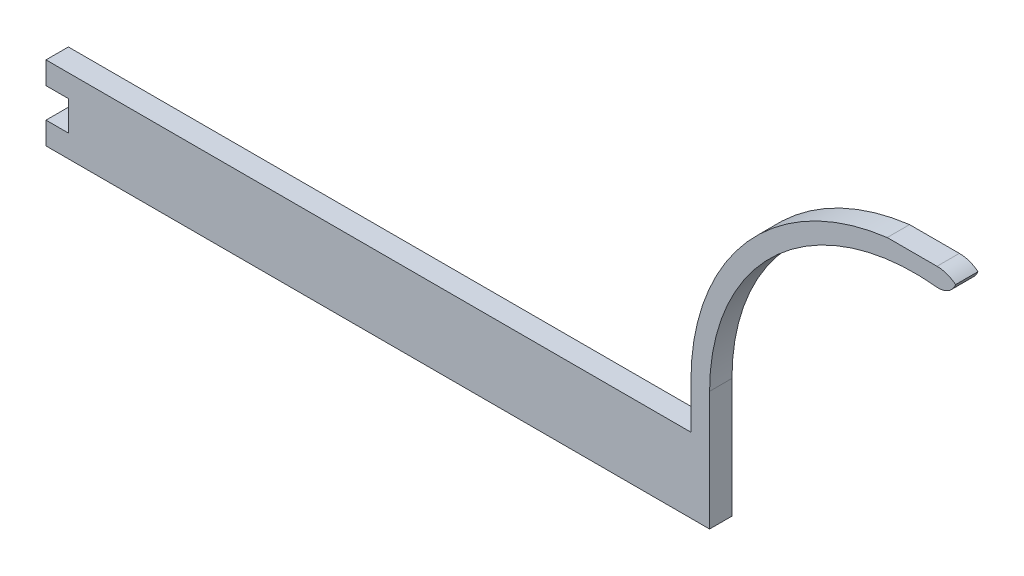
SolidWorks part; units mm, degrees
ref_plane "Спереди" through (0, 0, 0) normal (0, 0, 1) x (1, 0, 0)
ref_plane "Сверху" through (0, 0, 0) normal (0, 1, 0) x (1, 0, 0)
ref_plane "Справа" through (0, 0, 0) normal (1, 0, 0) x (0, 0, -1)
sketch "Эскиз2" plane through (0, 0, 0) normal (0, 0, 1) x (1, 0, 0)
  line L2 (0, 0) -> (0, 20) construction
  line L33 (0, 20) -> (167, 20)
  line L36 (187, 32) -> (167, 32) construction
  line L37 (167, 32) -> (167, 20)
  line L46 (233, 91.5474) -> (219.6446, 91.5474)
  line L49 (0, 20) -> (-6, 20)
  line L50 (-6, 20) -> (-6, 14)
  line L51 (-6, 14) -> (0, 14)
  line L52 (0, 14) -> (0, 6)
  line L53 (0, 6) -> (-6, 6)
  line L54 (-6, 6) -> (-6, 0)
  line L55 (-6, 0) -> (0, 0)
  line L63 (0, 0) -> (172, 0)
  line L64 (172, 0) -> (172, 32)
  arc A2 (238, 89.7924) -> (233, 91.5474) centre (233, 83.5474) ccw
  arc A8 (219.6446, 91.5474) -> (167, 32) centre (227, 32) ccw
  arc A11 (232.9062, 86.682) -> (172, 32) centre (227, 32) ccw
  arc A12 (232.9062, 86.682) -> (238, 89.7924) centre (233.4317, 91.5474) ccw
  dimension "D3" = 12
  dimension "D4" = 172
  dimension "D8" = 60
  dimension "D9" = 13.3554
  dimension "D7" = 55
  dimension "D10" = 8
  dimension "D2" = 20
  dimension "D6" = 69.7924
  dimension "D15" = 6
  dimension "D16" = 6
  dimension "D17" = 6
  dimension "D21" = 5
extrude "Бобышка-Вытянуть1" add sketch "Эскиз2" along normal blind 6
